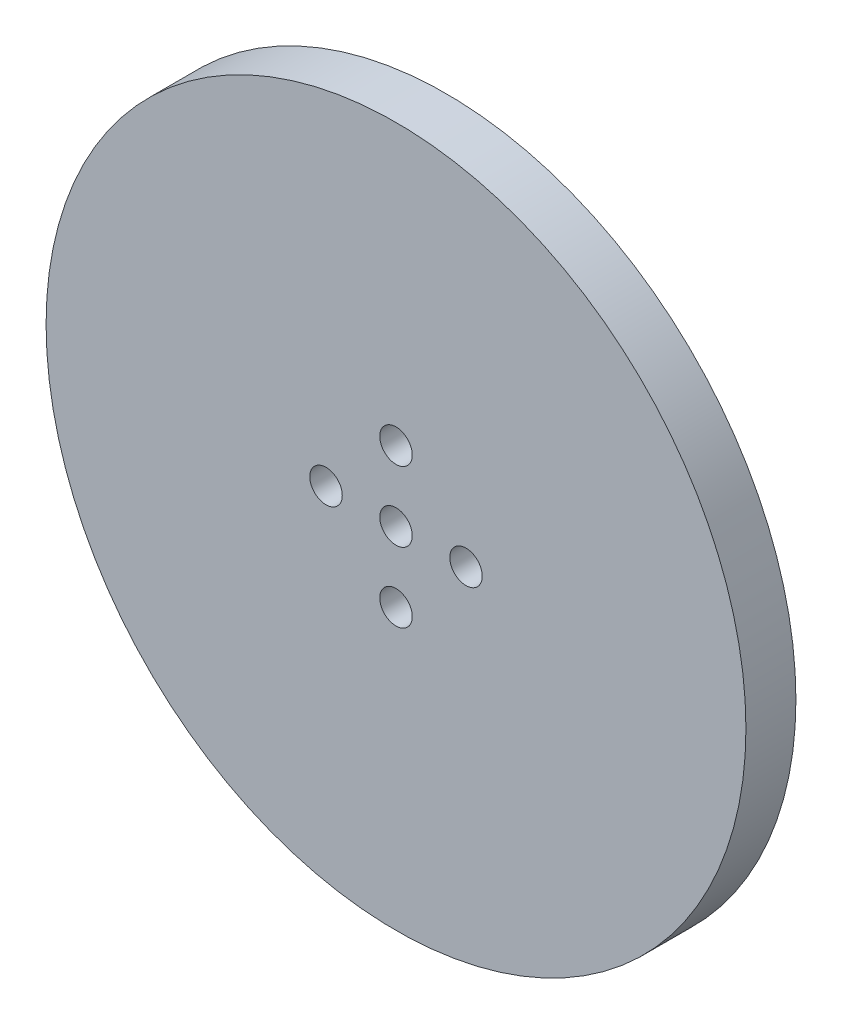
SolidWorks part; units mm, degrees
ref_plane "Plan de face" through (0, 0, 0) normal (0, 0, 1) x (1, 0, 0)
ref_plane "Plan de dessus" through (0, 0, 0) normal (0, 1, 0) x (1, 0, 0)
ref_plane "Plan de droite" through (0, 0, 0) normal (1, 0, 0) x (0, 0, -1)
sketch "Esquisse1" plane through (0, 0, 0) normal (0, 0, 1) x (1, 0, 0)
  circle A0 centre (0, 0) radius 35
  circle A1 centre (0, 0) radius 1.625
  circle A2 centre (0, 0) radius 7 construction
  circle A3 centre (0, 7) radius 1.625
  circle A4 centre (7, 0) radius 1.625
  circle A5 centre (0, -7) radius 1.625
  circle A6 centre (-7, 0) radius 1.625
  dimension "D1" = 70
  dimension "D2" = 14
  dimension "D3" = 3.25
  dimension "D4" = 4
extrude "Boss.-Extru.1" add sketch "Esquisse1" along normal blind 5
